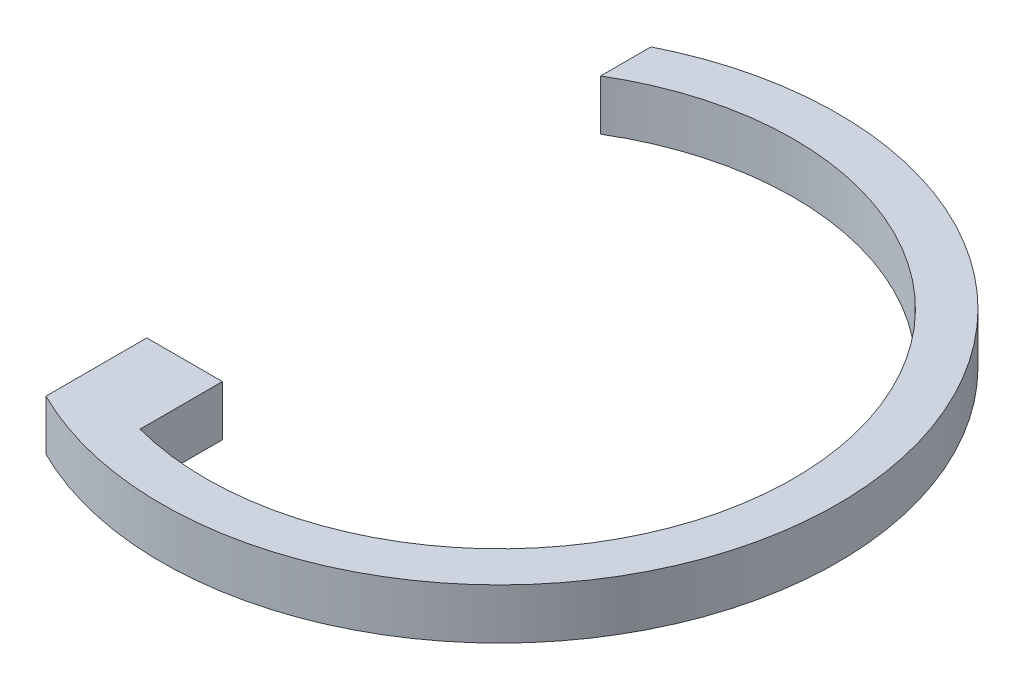
SolidWorks part; units mm, degrees
ref_plane "Front Plane" through (0, 0, 0) normal (0, 0, 1) x (1, 0, 0)
ref_plane "Top Plane" through (0, 0, 0) normal (0, 1, 0) x (1, 0, 0)
ref_plane "Right Plane" through (0, 0, 0) normal (1, 0, 0) x (0, 0, -1)
sketch "Sketch1" plane through (0, 0, 0) normal (0, 1, 0) x (1, 0, 0)
  line L0 (0, 0) -> (-20, 0) construction
  line L1 (-20, 0) -> (-20, 50) construction
  line L2 (-20, 0) -> (-20, -50) construction
  line L3 (-20, 50) -> (-20, 60)
  line L4 (-20, -50) -> (-20, -60)
  arc A0 (-20, 50) -> (-20, -50) centre (10, 0) cw
  arc A1 (-20, 60) -> (-20, -60) centre (10, 0) cw
  dimension "D5" = 0
  dimension "D1" = 30
  dimension "D2" = 50
  dimension "D3" = 10
  dimension "D4" = 10
extrude "Boss-Extrude1" add sketch "Sketch1" against normal blind 10
sketch "Sketch2" plane through (-20, 0, 0) normal (-1, 0, 0) x (0, 0, 1)
  line L1 (60, -10) -> (40, -10)
  line L2 (60, -10) -> (60, 0)
  line L3 (60, 0) -> (40, 0)
  line L4 (40, -10) -> (40, 0)
  dimension "D1" = 20
extrude "Boss-Extrude2" add sketch "Sketch2" against normal blind 15
